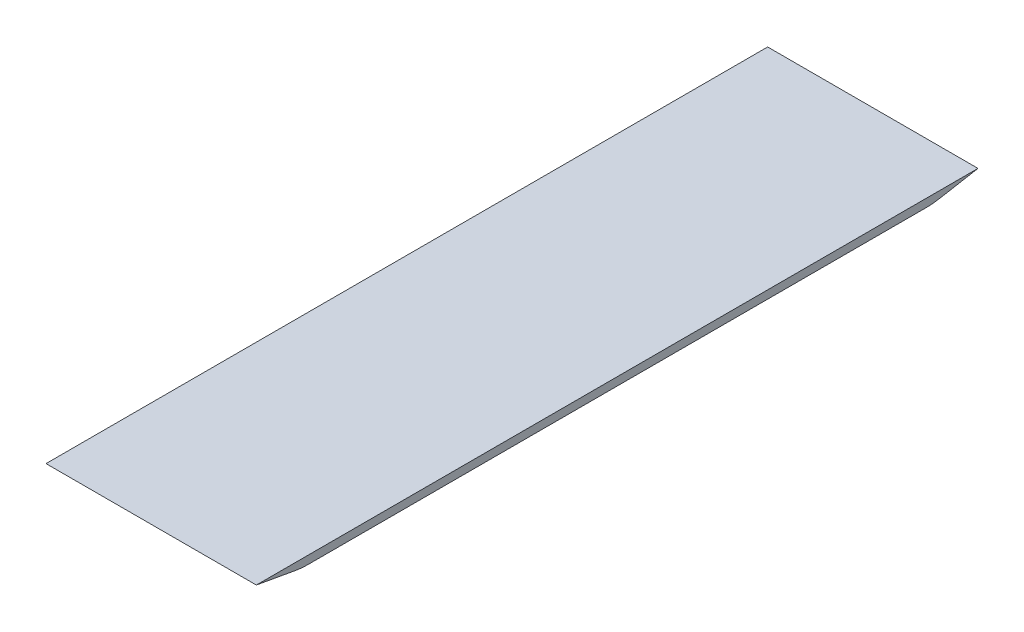
SolidWorks part; units mm, degrees
ref_plane "Front Plane" through (0, 0, 0) normal (0, 0, 1) x (1, 0, 0)
ref_plane "Top Plane" through (0, 0, 0) normal (0, 1, 0) x (1, 0, 0)
ref_plane "Right Plane" through (0, 0, 0) normal (1, 0, 0) x (0, 0, -1)
sketch "Sketch1" plane through (0, 0, 0) normal (1, 0, 0) x (0, 0, -1)
  line L0 (0, 0) -> (446, 0)
  line L1 (446, 0) -> (418, -5)
  line L2 (418, -5) -> (28, -5)
  line L3 (28, -5) -> (0, 0)
  dimension "D1" = 390
  dimension "D2" = 28
  dimension "D3" = 28
  dimension "D4" = 5
extrude "Boss-Extrude1" add sketch "Sketch1" along normal blind 130 contours L2 L3 L0 L1
fillet "Fillet1" radius 50 2 edges at (65, -5, -418) (65, -5, -28)
